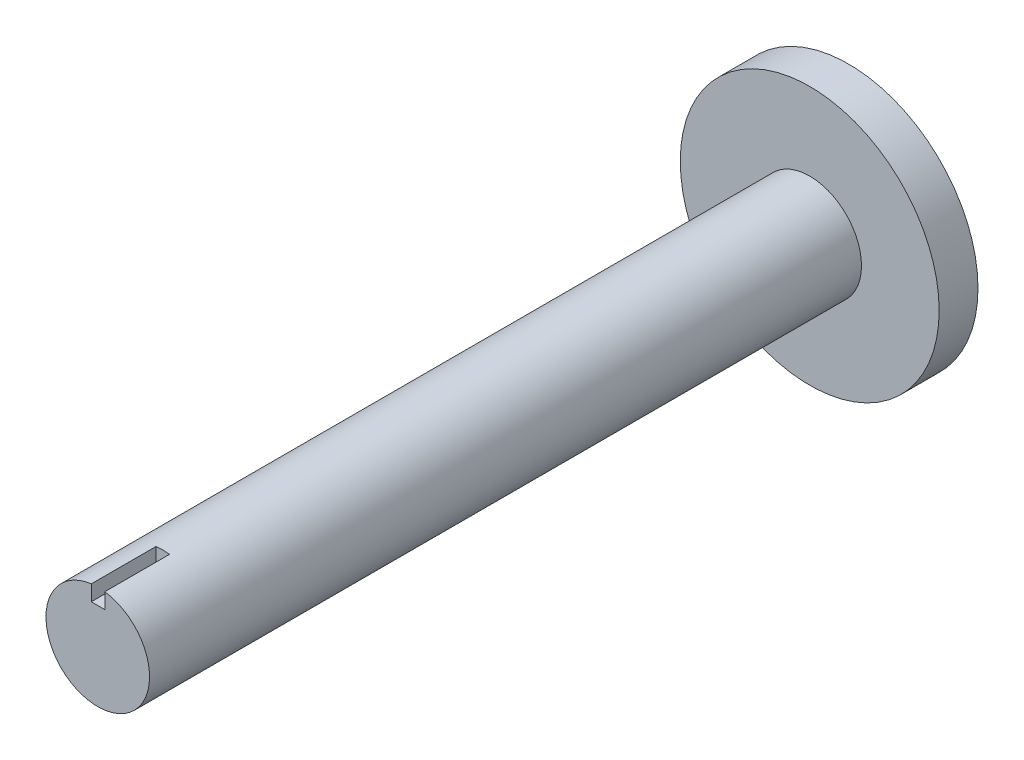
SolidWorks part; units mm, degrees
ref_plane "Front Plane" through (0, 0, 0) normal (0, 0, 1) x (1, 0, 0)
ref_plane "Top Plane" through (0, 0, 0) normal (0, 1, 0) x (1, 0, 0)
ref_plane "Right Plane" through (0, 0, 0) normal (1, 0, 0) x (0, 0, -1)
sketch "Sketch1" plane through (0, 0, 0) normal (0, 0, 1) x (1, 0, 0)
  circle A1 centre (0, 0) radius 10 construction
  circle A2 centre (0, 0) radius 10
extrude "Boss-Extrude1" add sketch "Sketch1" along normal blind 3
sketch "Sketch2" plane through (0, 0, 3) normal (0, 0, 1) x (1, 0, 0)
  circle A0 centre (0, 0) radius 4
  dimension "D1" = 8
extrude "Boss-Extrude2" add sketch "Sketch2" along normal blind 55
ref_plane "Plane1" through (0, 0, 53) normal (0, 0, 1) x (1, 0, 0)
sketch "Sketch3" plane through (0, 0, 53) normal (0, 0, 1) x (1, 0, 0)
  line L1 (-0.5, 3.9686) -> (-0.5, 2.7686)
  line L2 (-0.5, 2.7686) -> (0.5433, 2.7686)
  line L3 (0.5433, 2.7686) -> (0.5433, 3.9629)
  circle A0 centre (0, 0) radius 4 construction
  arc A1 (0.5433, 3.9629) -> (-0.5, 3.9686) centre (0, 0) ccw
  dimension "D1" = 1.2
extrude "Cut-Extrude1" cut sketch "Sketch3" along normal blind 10
